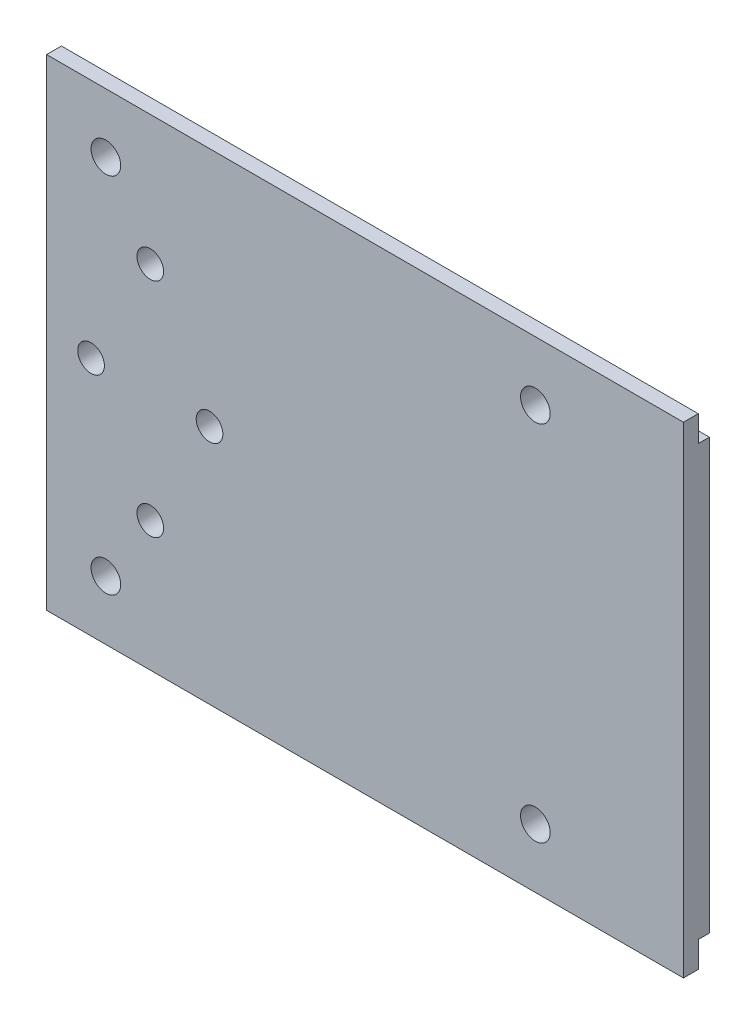
SolidWorks part; units mm, degrees
ref_plane "Front Plane" through (0, 0, 0) normal (0, 0, 1) x (1, 0, 0)
ref_plane "Top Plane" through (0, 0, 0) normal (0, 1, 0) x (1, 0, 0)
ref_plane "Right Plane" through (0, 0, 0) normal (1, 0, 0) x (0, 0, -1)
sketch "Sketch1" plane through (0, 0, 0) normal (0, 0, 1) x (1, 0, 0)
  line L0 (-29, 29.5) -> (36, 29.5) construction
  line L1 (-46.5, 29) -> (36, 29)
  line L2 (-46.5, 29) -> (-46.5, -29)
  line L3 (-46.5, -29) -> (36, -29)
  line L4 (36, 29) -> (36, -29)
  line L5 (-47, -27.5) -> (-47, 27.5) construction
  line L6 (36, 29.5) -> (36, 30.5) construction
  line L7 (4.4988, -29.5) -> (-45, -29.5) construction
  dimension "D1" = 0.5
  dimension "D2" = 0.5
  dimension "D3" = 0
  dimension "D4" = 0.5
extrude "Boss-Extrude1" add sketch "Sketch1" against normal blind 1.5
sketch "Sketch2" plane through (0, 0, 0) normal (0, 0, 1) x (1, 0, 0)
  line L0 (34, 32.5) -> (-48, 32.5) construction
  line L1 (-50, 32.5) -> (36, 32.5)
  line L2 (-50, 32.5) -> (-50, -32.5)
  line L3 (-50, -32.5) -> (36, -32.5)
  line L4 (36, 32.5) -> (36, -32.5)
  line L5 (-50, 30.5) -> (-50, -30.5) construction
  line L6 (-48, -32.5) -> (34, -32.5) construction
  line L7 (36, -30.5) -> (36, -29.5) construction
extrude "Boss-Extrude2" add sketch "Sketch2" along normal blind 2
sketch "Sketch3" plane through (0, 0, 2) normal (0, 0, 1) x (1, 0, 0)
  circle A0 centre (-42, 24.5) radius 2
  circle A1 centre (16, 24.5) radius 2
  circle A2 centre (16, -24.5) radius 2
  circle A3 centre (-42, -24.5) radius 2
  dimension "D1" = 4
extrude "Cut-Extrude1" cut sketch "Sketch3" against normal through all
sketch "Sketch4" plane through (0, 0, 2) normal (0, 0, 1) x (1, 0, 0)
  line L0 (-50, 0) -> (0, 0) construction
  line L1 (-50, 32.5) -> (-50, -32.5) construction
  line L2 (-28, 0) -> (-44, 0) construction
  line L3 (-28, -1.8) -> (-44, -1.8) construction
  line L4 (-36, -1.8) -> (-36, 15) construction
  line L5 (-36, 1.8) -> (-36, -15) construction
  circle A0 centre (-44, 0) radius 1.8
  circle A1 centre (-28, 0) radius 1.8
  circle A2 centre (-42, 24.5) radius 2 construction
  circle A3 centre (-36, 15) radius 1.8
  circle A4 centre (-36, -15) radius 1.8
  dimension "D1" = 3.6
  dimension "D2" = 3.6
  dimension "D3" = 16
  dimension "D5" = 3.6
  dimension "D4" = 14
  dimension "D6" = 15
extrude "Cut-Extrude2" cut sketch "Sketch4" against normal through all
sketch "Sketch5" plane through (0, 0, -1.5) normal (0, 0, -1) x (-1, 0, 0)
  circle A0 centre (-16, 24.5) radius 4
  circle A1 centre (-16, -24.5) radius 4
  circle A2 centre (42, -24.5) radius 4
  circle A3 centre (42, 24.5) radius 4
  dimension "D1" = 8
extrude "Cut-Extrude3" cut sketch "Sketch5" against normal blind 0.5
